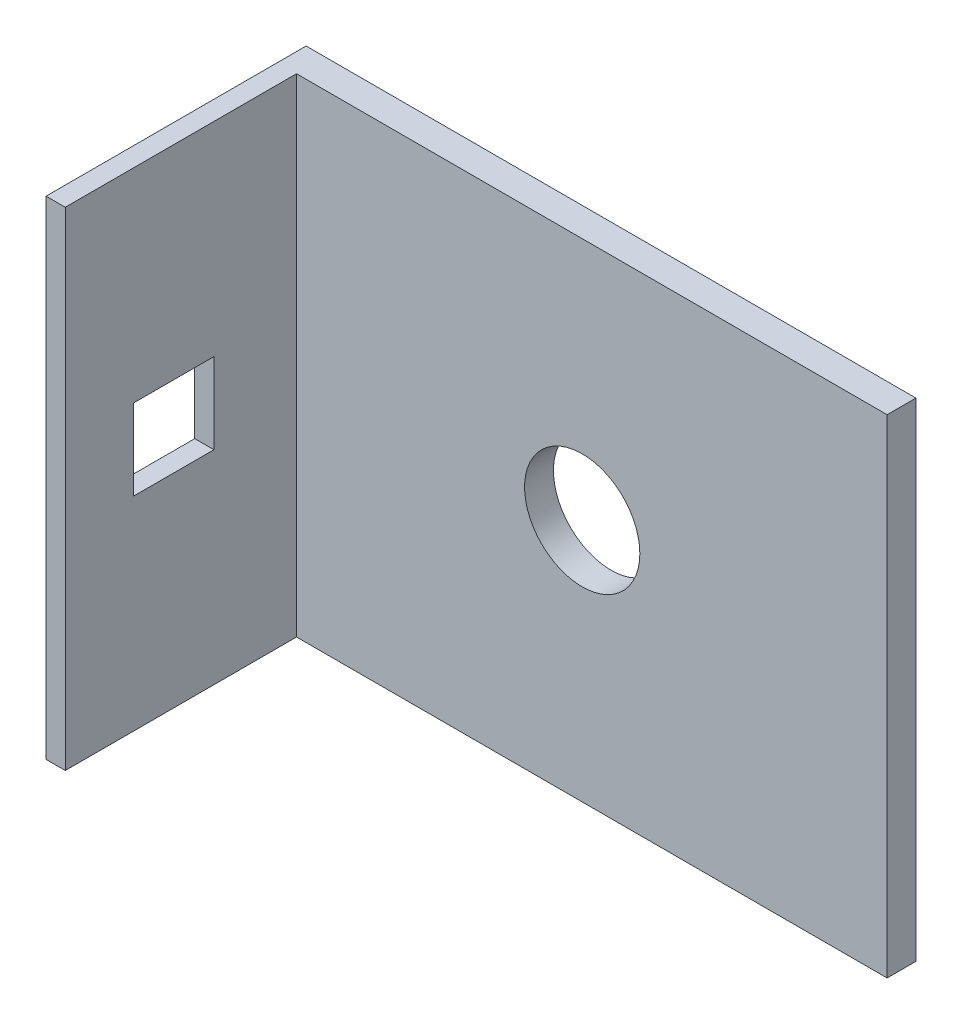
SolidWorks part; units mm, degrees
ref_plane "Front Plane" through (0, 0, 0) normal (0, 0, 1) x (1, 0, 0)
ref_plane "Top Plane" through (0, 0, 0) normal (0, 1, 0) x (1, 0, 0)
ref_plane "Right Plane" through (0, 0, 0) normal (1, 0, 0) x (0, 0, -1)
sketch "Sketch1" plane through (0, 0, 0) normal (0, 0, 1) x (1, 0, 0)
  line L1 (-31.75, 25.4) -> (31.75, 25.4)
  line L2 (-31.75, 25.4) -> (-31.75, -25.4)
  line L3 (-31.75, -25.4) -> (31.75, -25.4)
  line L4 (31.75, 25.4) -> (31.75, -25.4)
  circle A0 centre (0, 0) radius 6
  dimension "D1" = 12
  dimension "D2" = 31.75
  dimension "D3" = 63.5
  dimension "D4" = 25.4
  dimension "D5" = 50.8
extrude "Boss-Extrude1" add sketch "Sketch1" along normal blind 3
sketch "Sketch2" plane through (0, 0, 3) normal (0, 0, 1) x (1, 0, 0)
  line L5 (-31.75, -25.4) -> (31.75, -25.4) construction
  line L6 (-31.75, 25.4) -> (-29.75, 25.4)
  line L7 (-31.75, 25.4) -> (-31.75, -25.4)
  line L8 (-31.75, -25.4) -> (-29.75, -25.4)
  line L9 (-29.75, 25.4) -> (-29.75, -25.4)
  dimension "D1" = 2
extrude "Boss-Extrude2" add sketch "Sketch2" along normal blind 24.082
sketch "Sketch3" plane through (-31.75, 0, 0) normal (-1, 0, 0) x (0, 0, 1)
  line L0 (0, 25.4) -> (0, -25.4) construction
  line L1 (20, 4.191) -> (11.6, 4.191)
  line L2 (20, 4.191) -> (20, -4.209)
  line L3 (20, -4.209) -> (11.6, -4.209)
  line L4 (11.6, 4.191) -> (11.6, -4.209)
  line L5 (27.082, 25.4) -> (0, 25.4) construction
  dimension "D1" = 8.4
  dimension "D2" = 8.4
  dimension "D3" = 20
  dimension "D4" = 21.209
extrude "Cut-Extrude1" cut sketch "Sketch3" against normal up to surface (2 mm away) up to face at (-29.75, 0, 15.041)
